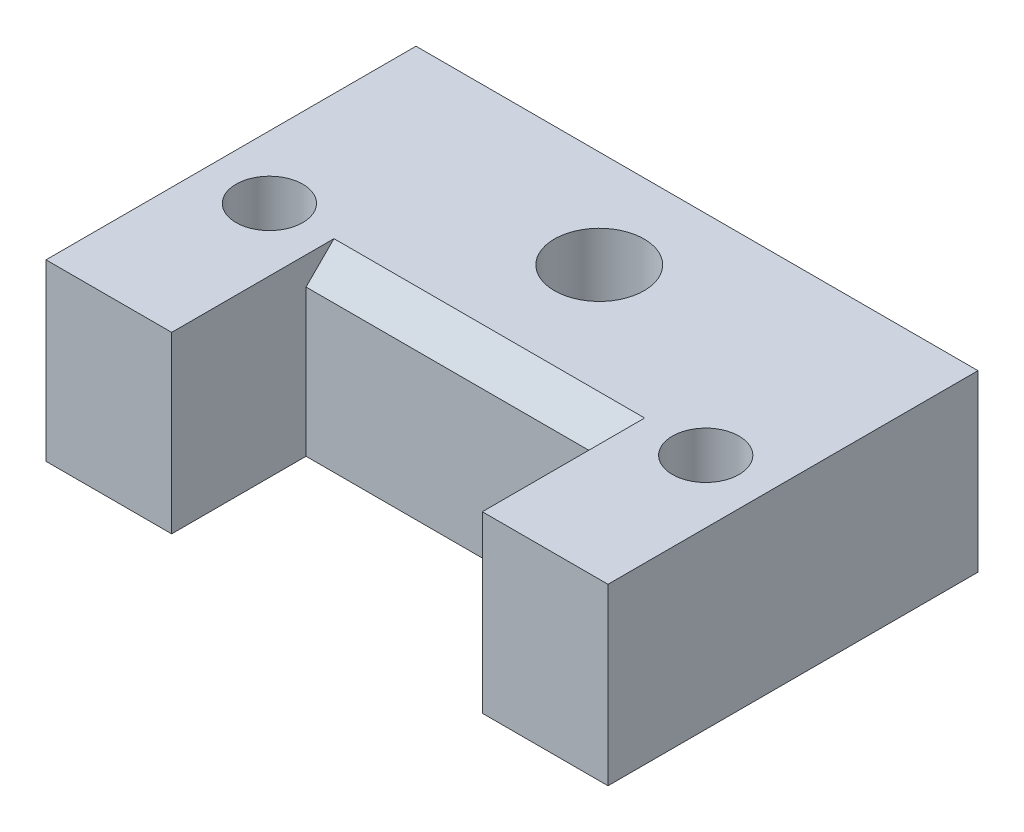
SolidWorks part; units mm, degrees
material "C.R.S."
ref_plane "Alzado" through (0, 0, 0) normal (0, 0, 1) x (1, 0, 0)
ref_plane "Planta" through (0, 0, 0) normal (0, 1, 0) x (1, 0, 0)
ref_plane "Vista lateral" through (0, 0, 0) normal (1, 0, 0) x (0, 0, -1)
sketch "Croquis2" plane through (0, 0, 0) normal (0, 1, 0) x (1, 0, 0)
  line L1 (-20.447, 13.462) -> (20.447, 13.462)
  line L2 (-20.447, 13.462) -> (-20.447, -13.462)
  line L3 (-20.447, -13.462) -> (20.447, -13.462)
  line L4 (20.447, 13.462) -> (20.447, -13.462)
  line L5 (-20.447, 13.462) -> (20.447, -13.462) construction
  line L6 (-20.447, -13.462) -> (20.447, 13.462) construction
  point P0 (0, 0)
  dimension "D1" = 26.924
  dimension "D2" = 40.894
extrude "Saliente-Extruir1" add sketch "Croquis2" along normal blind 12.7
sketch "Croquis3" plane through (0, 12.7, 0) normal (0, 1, 0) x (1, 0, 0)
  line L0 (-20.447, -13.462) -> (20.447, -13.462) construction
  line L1 (-11.303, -13.462) -> (11.303, -13.462)
  line L2 (-11.303, -13.462) -> (-11.303, -3.683)
  line L3 (-11.303, -3.683) -> (11.303, -3.683)
  line L4 (11.303, -13.462) -> (11.303, -3.683)
  line L5 (0, -3.683) -> (0, -13.462) construction
  line L6 (-11.303, -8.5725) -> (11.303, -8.5725) construction
  line L7 (20.447, 13.462) -> (-20.447, 13.462) construction
  point P472 (0, -8.5725)
  dimension "D1" = 22.606
  dimension "D2" = 17.145
extrude "Cortar-Extruir1" cut sketch "Croquis3" against normal blind 12.7
sketch "Croquis6" plane through (0, 12.7, 0) normal (0, 1, 0) x (1, 0, 0)
  line L0 (-15.875, -1.778) -> (15.875, -1.778) construction
  line L1 (20.447, 13.462) -> (-20.447, 13.462) construction
  circle A0 centre (-15.875, -1.778) radius 2.4257
  circle A1 centre (15.875, -1.778) radius 2.4257
  point P4 (0, -1.778)
  dimension "D3" = 4.8514
  dimension "D1" = 31.75
  dimension "D2" = 15.24
extrude "Cortar-Extruir2" cut sketch "Croquis6" against normal blind 12.7
sketch "Croquis7" plane through (0, 12.7, 0) normal (0, 1, 0) x (1, 0, 0)
  circle A0 centre (15.875, -1.778) radius 2.4257 construction
  point P0 (0, 6.35)
  dimension "D1" = 8.128
hole_wizard "Taladro roscado 5/16-181" positions "Croquis7" profile "Croquis8" tap size "5/16-18" standard "Ansi Inch" end condition through all
sketch "Croquis8" plane through (0, 12.7, -6.35) normal (1, 0, 0) x (0, 0, 1)
  line L0 (0, 0) -> (0, 12.7)
  line L1 (0, 12.7) -> (3.2639, 12.7)
  line L2 (3.2639, 12.7) -> (3.2639, 0)
  line L5 (3.2639, 0) -> (0, 0)
  line L11 (0, -6.35) -> (0, 107.95) construction
  dimension "Diámetro de perforador para roscar hasta el siguiente" = 6.5278
  dimension "Profundidad de perforador para roscar hasta el siguiente" = 12.7
cosmetic thread "Rosca de taladro1" parameters "D2"=7.9375
chamfer "Chaflán1" distance 2.032 angle 45 1 edges at (0, 12.7, 3.683)
